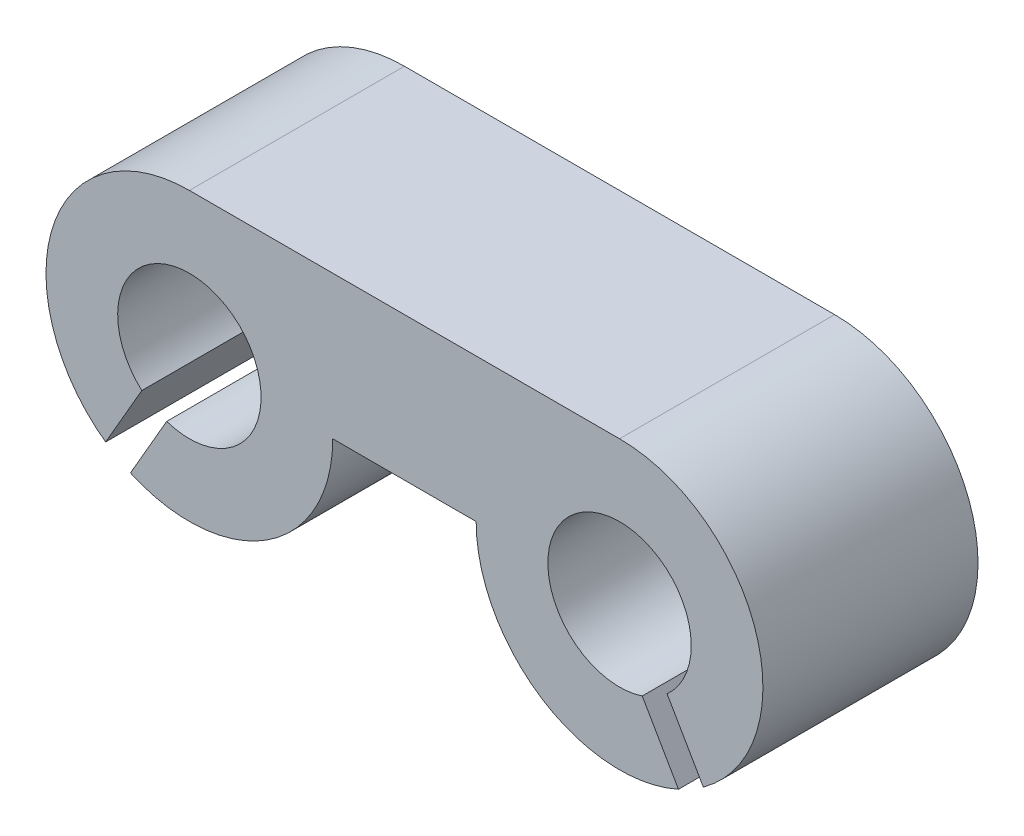
SolidWorks part; units mm, degrees
ref_plane "Front Plane" through (0, 0, 0) normal (0, 0, 1) x (1, 0, 0)
ref_plane "Top Plane" through (0, 0, 0) normal (0, 1, 0) x (1, 0, 0)
ref_plane "Right Plane" through (0, 0, 0) normal (1, 0, 0) x (0, 0, -1)
sketch "Sketch2" plane through (0, 0, 0) normal (0, 0, 1) x (1, 0, 0)
  line L0 (-15, 0) -> (15, 0) construction
  line L1 (-5, 10) -> (-15, 10)
  line L2 (-5, 10) -> (5, 10)
  line L3 (5, 10) -> (15, 10)
  line L4 (-5, 0) -> (5, 0)
  line L5 (-5, 10) -> (-5, 0) construction
  line L6 (5, 0) -> (5, 10) construction
  arc A0 (-15, 10) -> (-5, 0) centre (-15, 0) ccw
  arc A1 (5, 0) -> (15, 10) centre (15, 0) ccw
  arc A2 (-15, 10) -> (-5, 0) centre (-15, 0) cw construction
  arc A3 (15, 10) -> (5, 0) centre (15, 0) ccw construction
  dimension "D1" = 20
  dimension "D2" = 30
  dimension "D3" = 10
extrude "Boss-Extrude1" add sketch "Sketch2" along normal blind 15
sketch "Sketch3" plane through (0, 0, 15) normal (0, 0, 1) x (1, 0, 0)
  circle A0 centre (-15, 0) radius 5
  circle A1 centre (15, 0) radius 5
  dimension "D1" = 10
extrude "Cut-Extrude1" cut sketch "Sketch3" against normal through all
sketch "Sketch4" plane through (0, 0, 15) normal (0, 0, 1) x (1, 0, 0)
  line L0 (-14.134, -0.5) -> (-15.866, 0.5)
  line L1 (-14.134, -0.5) -> (-19.134, -9.1603)
  line L2 (-15.866, 0.5) -> (-20.866, -8.1603)
  line L3 (-19.134, -9.1603) -> (-20.866, -8.1603)
  line L4 (-5, 0) -> (5, 0) construction
  line L5 (14.134, -0.5) -> (15.866, 0.5)
  line L6 (14.134, -0.5) -> (19.134, -9.1603)
  line L7 (15.866, 0.5) -> (20.866, -8.1603)
  line L8 (19.134, -9.1603) -> (20.866, -8.1603)
  arc A0 (-15, 10) -> (-5, 0) centre (-15, 0) ccw construction
  arc A1 (5, 0) -> (15, 10) centre (15, 0) ccw construction
  point P0 (-15, 0)
  point P3 (15, 0)
  dimension "D1" = 2
  dimension "D2" = 120
  dimension "D3" = 120
extrude "Cut-Extrude2" cut sketch "Sketch4" against normal through all
